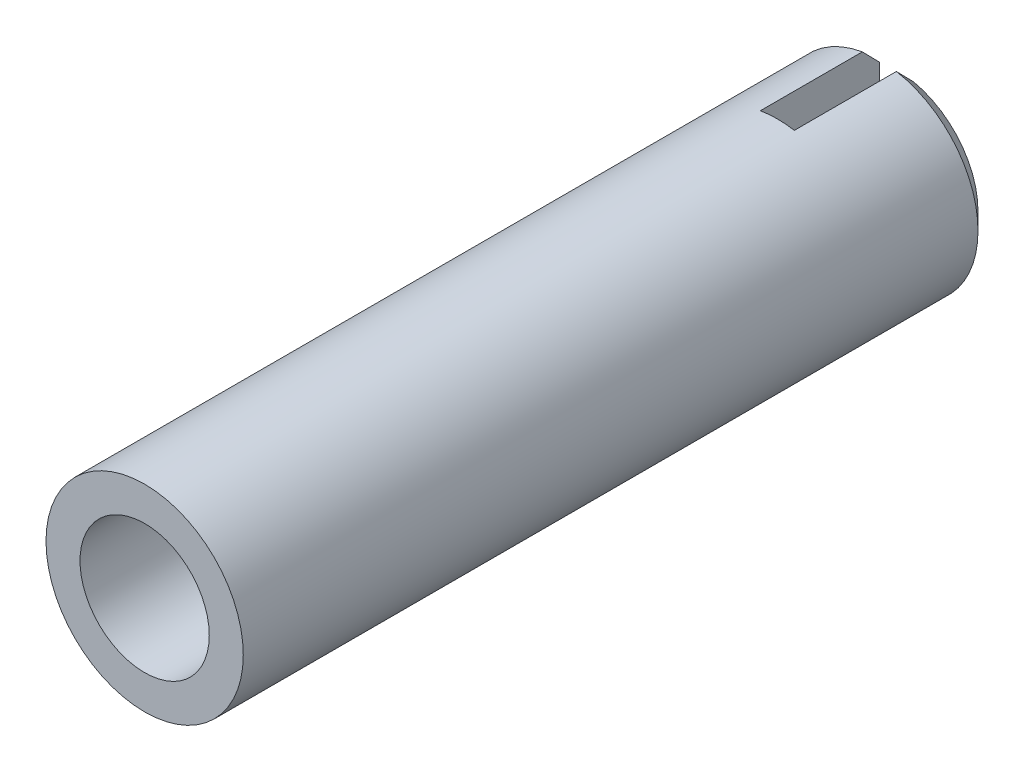
SolidWorks part; units mm, degrees
ref_plane "前视基准面" through (0, 0, 0) normal (0, 0, 1) x (1, 0, 0)
ref_plane "上视基准面" through (0, 0, 0) normal (0, 1, 0) x (1, 0, 0)
ref_plane "右视基准面" through (0, 0, 0) normal (1, 0, 0) x (0, 0, -1)
other "Configuration Table"
sketch "草图1" plane through (0, 0, 0) normal (0, 0, 1) x (1, 0, 0)
  circle A0 centre (0, 0) radius 2.9
  dimension "D1" = 5.8
extrude "拉伸-薄壁1" add sketch "草图1" against normal blind 22.1 thin thin type one direction reverse wall 1
chamfer "倒角1" distance 0.5 angle 45 1 edges at (2.9, 0, -22.1)
sketch "草图3" plane through (0, 0, -22.1) normal (0, 0, -1) x (-1, 0, 0)
  line L0 (1.0678, 0) -> (-1.189, 0) construction
  line L1 (0.5, -1.2811) -> (-0.5, -1.2811)
  line L2 (0.5, 3.2654) -> (-0.5, 3.2654)
  line L3 (0.5, 3.2654) -> (0.5, 1.2811)
  line L4 (0.5, 1.2811) -> (-0.5, 1.2811)
  line L5 (-0.5, 3.2654) -> (-0.5, 1.2811)
  line L6 (0.5, 3.2654) -> (-0.5, 1.2811) construction
  line L7 (0.5, 1.2811) -> (-0.5, 3.2654) construction
  line L8 (-0.5, -3.2654) -> (-0.5, -1.2811)
  line L9 (0.5, -3.2654) -> (-0.5, -3.2654)
  line L10 (0.5, -3.2654) -> (0.5, -1.2811)
  line L11 (0, 0) -> (0, 1.6775) construction
  point P3 (0, 2.2733)
  point P15 (0, 0)
  dimension "D1" = 1
extrude "切除-拉伸1" cut sketch "草图3" against normal blind 3.5
